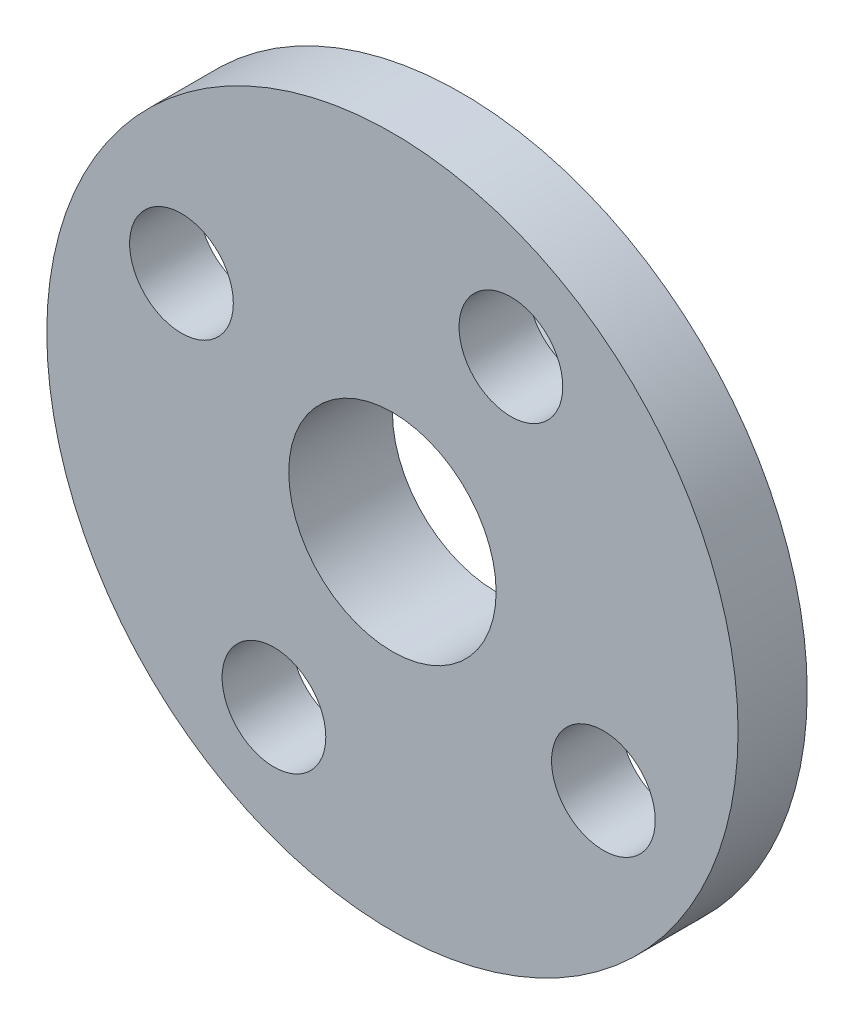
SolidWorks part; units mm, degrees
ref_plane "前视基准面" through (0, 0, 0) normal (0, 0, 1) x (1, 0, 0)
ref_plane "上视基准面" through (0, 0, 0) normal (0, 1, 0) x (1, 0, 0)
ref_plane "右视基准面" through (0, 0, 0) normal (1, 0, 0) x (0, 0, -1)
sketch "草图1" plane through (0, 0, 0) normal (0, 0, 1) x (1, 0, 0)
  circle A0 centre (0, 0) radius 5
  circle A1 centre (0, 0) radius 3
  dimension "D1" = 10
  dimension "D2" = 6
extrude "凸台-拉伸1" add sketch "草图1" along normal blind 1
sketch "草图2" plane through (0, 0, 1) normal (0, 0, 1) x (1, 0, 0)
  circle A0 centre (0, 0) radius 10
  circle A1 centre (0, 0) radius 3 construction
  circle A2 centre (0, 0) radius 3
  dimension "D1" = 20
extrude "凸台-拉伸2" add sketch "草图2" along normal blind 2
sketch "草图3" plane through (0, 0, 3) normal (0, 0, 1) x (1, 0, 0)
  line L0 (0, 0) -> (3.4276, 6.1034) construction
  circle A0 centre (3.4276, 6.1034) radius 1.5
  circle A1 centre (6.1034, -3.4276) radius 1.5
  circle A2 centre (-3.4276, -6.1034) radius 1.5
  circle A3 centre (-6.1034, 3.4276) radius 1.5
  point P13 (0, 0)
  dimension "D1" = 3
  dimension "D2" = 7
  dimension "D3" = 4
extrude "切除-拉伸1" cut sketch "草图3" against normal through all
